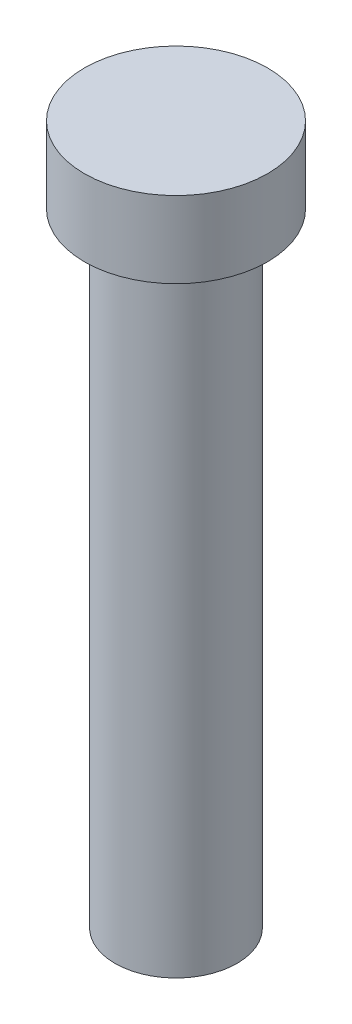
SolidWorks part; units mm, degrees
material "1060 Alloy"
ref_plane "Front Plane" through (0, 0, 0) normal (0, 0, 1) x (1, 0, 0)
ref_plane "Top Plane" through (0, 0, 0) normal (0, 1, 0) x (1, 0, 0)
ref_plane "Right Plane" through (0, 0, 0) normal (1, 0, 0) x (0, 0, -1)
sketch "Sketch1" plane through (0, 0, 0) normal (0, 1, 0) x (1, 0, 0)
  circle A0 centre (0, 0) radius 4
  dimension "D1" = 8
extrude "Boss-Extrude1" add sketch "Sketch1" along normal blind 40.8
sketch "Sketch2" plane through (0, 40.8, 0) normal (0, 1, 0) x (1, 0, 0)
  circle A0 centre (0, 0) radius 6
  dimension "D1" = 12
extrude "Boss-Extrude2" add sketch "Sketch2" along normal blind 5
sketch "Sketch3" plane through (0, 0, 0) normal (0, -1, 0) x (1, 0, 0)
  circle A0 centre (0, 0) radius 1.5
  dimension "D1" = 3
extrude "Cut-Extrude1" cut sketch "Sketch3" against normal blind 15
